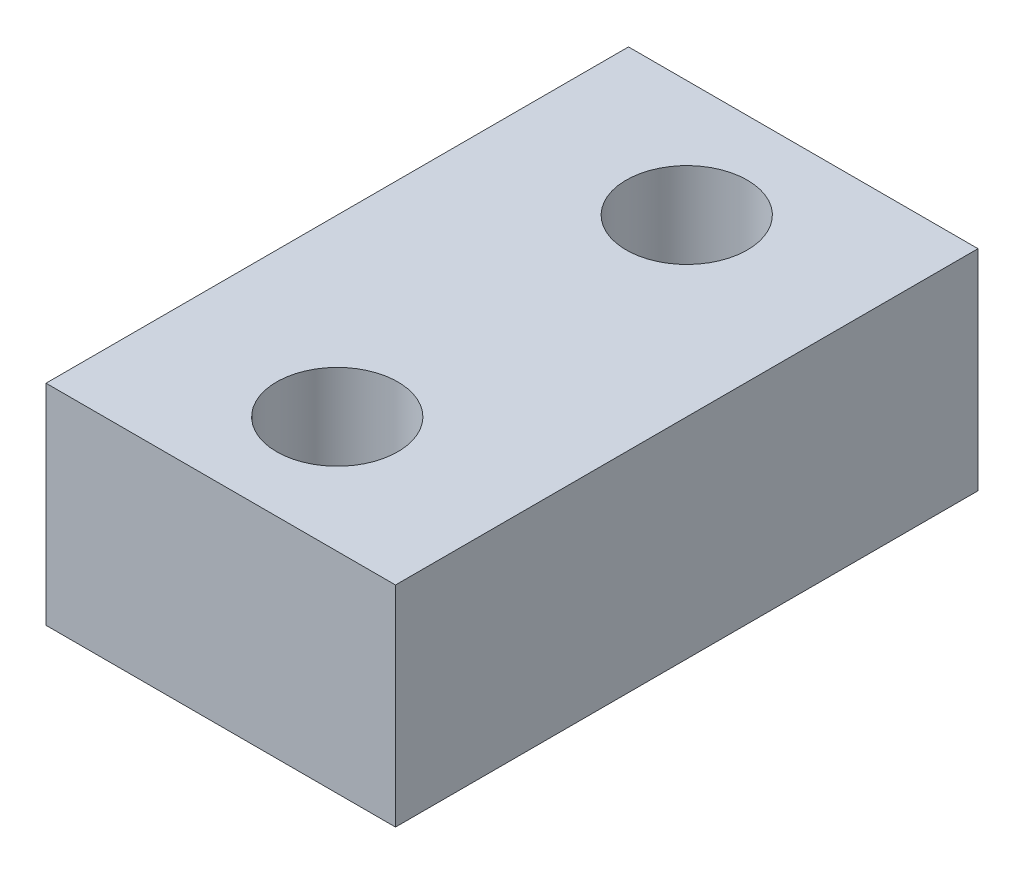
SolidWorks part; units mm, degrees
ref_plane "前视基准面" through (0, 0, 0) normal (0, 0, 1) x (1, 0, 0)
ref_plane "上视基准面" through (0, 0, 0) normal (0, 1, 0) x (1, 0, 0)
ref_plane "右视基准面" through (0, 0, 0) normal (1, 0, 0) x (0, 0, -1)
other "Configuration Table"
sketch "草图1" plane through (0, 0, 0) normal (0, 1, 0) x (1, 0, 0)
  line L1 (-32.5, 12.5) -> (32.5, 12.5)
  line L2 (-32.5, 12.5) -> (-32.5, -12.5)
  line L3 (-32.5, -12.5) -> (32.5, -12.5)
  line L4 (32.5, 12.5) -> (32.5, -12.5)
  line L5 (0, -12.5) -> (0, 12.5) construction
  line L6 (-32.5, 0) -> (32.5, 0) construction
  point P0 (0, 0)
  dimension "D1" = 25
  dimension "D2" = 65
extrude "凸台-拉伸1" add sketch "草图1" along normal blind 4
sketch "草图2" plane through (0, 4, 0) normal (0, 1, 0) x (1, 0, 0)
  line L0 (-32.5, -12.5) -> (32.5, -12.5) construction
  line L1 (-7.5, 12.5) -> (7.5, 12.5)
  line L2 (-7.5, 12.5) -> (-7.5, -12.5)
  line L3 (-7.5, -12.5) -> (7.5, -12.5)
  line L4 (7.5, 12.5) -> (7.5, -12.5)
  line L5 (0, -12.5) -> (0, 12.5) construction
  line L6 (-7.5, 0) -> (7.5, 0) construction
  point P0 (0, 0)
  dimension "D1" = 15
extrude "凸台-拉伸2" add sketch "草图2" along normal blind 13
sketch "草图3" plane through (0, 0, 0) normal (0, -1, 0) x (1, 0, 0)
  line L0 (0, 12.5) -> (0, -12.5) construction
  line L1 (-32.5, 12.5) -> (32.5, 12.5) construction
  line L2 (32.5, -12.5) -> (-32.5, -12.5) construction
  line L3 (-32.5, 0) -> (32.5, 0) construction
  line L4 (-32.5, -12.5) -> (-32.5, 12.5) construction
  line L5 (32.5, 12.5) -> (32.5, -12.5) construction
  circle A0 centre (0, -7.5) radius 2.6
  circle A1 centre (0, 7.5) radius 2.6
  circle A2 centre (-22, 0) radius 4
  circle A3 centre (22, 0) radius 4
  dimension "D1" = 5.2
  dimension "D3" = 8
  dimension "D2" = 5
  dimension "D4" = 22
extrude "切除-拉伸1" cut sketch "草图3" against normal through all
sketch "草图5" plane through (0, 0, 12.5) normal (0, 0, 1) x (1, 0, 0)
  line L0 (7.5, 17) -> (7.5, 4) construction
  line L1 (-7.5, 4) -> (7.5, 4)
  line L2 (-7.5, 4) -> (-7.5, 8)
  line L3 (-7.5, 8) -> (7.5, 8)
  line L4 (7.5, 4) -> (7.5, 8)
  dimension "D1" = 4
extrude "凸台-拉伸3" add sketch "草图5" along normal blind 6
sketch "草图6" plane through (0, 4, 0) normal (0, -1, 0) x (1, 0, 0)
  line L0 (0, 18.5) -> (0, 12.5) construction
  line L1 (-7.5, 18.5) -> (7.5, 18.5) construction
  line L2 (-32.5, 12.5) -> (32.5, 12.5) construction
  line L3 (-7.5, 18.5) -> (-7.5, 12.5) construction
  circle A0 centre (-4.5, 15.5) radius 1.25
  circle A1 centre (4.5, 15.5) radius 1.25
  point P11 (-7.5, 15.5)
  dimension "D1" = 2.5
  dimension "D2" = 3
extrude "切除-拉伸3" cut sketch "草图6" against normal through all
ref_plane "基准面2" through (0, 0, 0) normal (0, 0, 1) x (1, 0, 0)
mirror "镜向2" about plane through (0, 0, 0) normal (0, 0, 1) of "凸台-拉伸3", "切除-拉伸3"
fillet "圆角2" radius 3 4 edges at (-7.5, 6, -18.5) (7.5, 6, -18.5) (-7.5, 6, 18.5) (7.5, 6, 18.5)
sketch "草图7" plane through (0, 0, -12.5) normal (0, 0, -1) x (-1, 0, 0)
  line L6 (32.5, 4) -> (7.5, 4)
  line L7 (7.5, 4) -> (-7.5, 4)
  line L8 (-7.5, 4) -> (-32.5, 4)
  line L9 (-32.5, 4) -> (-32.5, 0)
  line L10 (-32.5, 0) -> (32.5, 0)
  line L11 (32.5, 0) -> (32.5, 4)
  line L12 (32.5, 4) -> (7.5, 4)
  line L13 (7.5, 4) -> (-7.5, 4)
  line L14 (-7.5, 4) -> (-32.5, 4)
  line L15 (-32.5, 4) -> (-32.5, 0)
  line L16 (-32.5, 0) -> (32.5, 0)
  line L17 (32.5, 0) -> (32.5, 4)
  dimension "D1" = 0
extrude "切除-拉伸4" cut sketch "草图7" against normal through all
sketch "草图9" plane through (0, 0, 18.5) normal (0, 0, 1) x (1, 0, 0)
  line L1 (-7.5, 8) -> (7.5, 8)
  line L2 (-7.5, 8) -> (-7.5, 4)
  line L3 (-7.5, 4) -> (7.5, 4)
  line L4 (7.5, 8) -> (7.5, 4)
extrude "切除-拉伸5" cut sketch "草图9" against normal through all
